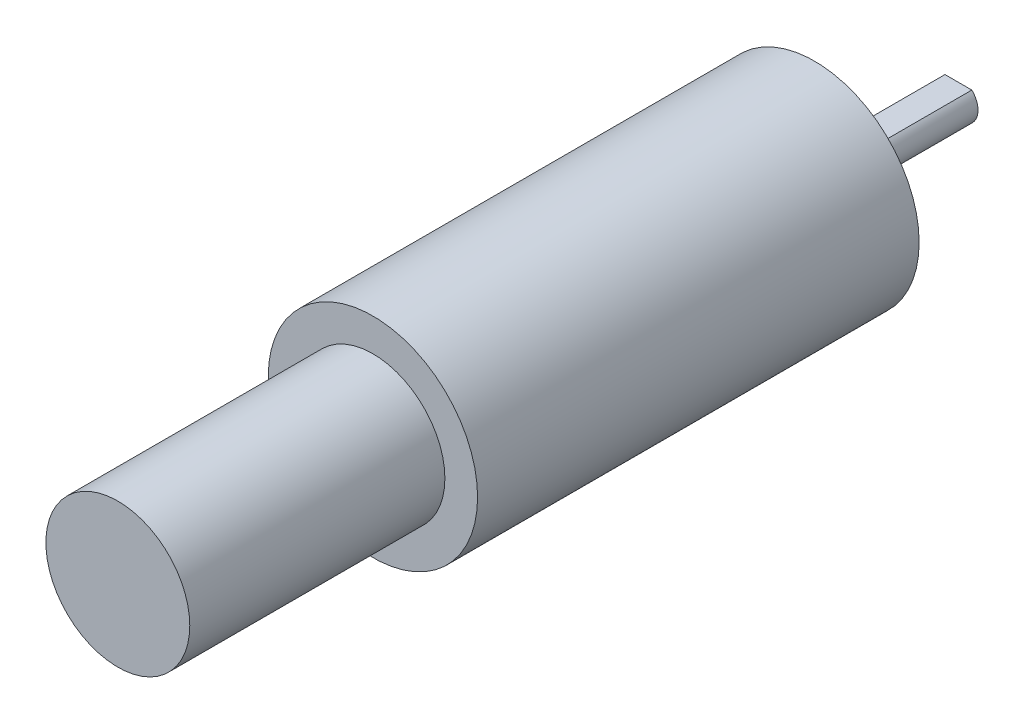
SolidWorks part; units mm, degrees
ref_plane "Front Plane" through (0, 0, 0) normal (0, 0, 1) x (1, 0, 0)
ref_plane "Top Plane" through (0, 0, 0) normal (0, 1, 0) x (1, 0, 0)
ref_plane "Right Plane" through (0, 0, 0) normal (1, 0, 0) x (0, 0, -1)
sketch "Sketch1" plane through (0, 0, 0) normal (0, 0, 1) x (1, 0, 0)
  circle A0 centre (0, 0) radius 16
  dimension "D1" = 32
extrude "Boss-Extrude1" add sketch "Sketch1" along normal blind 67.5
sketch "Sketch2" plane through (0, 0, 0) normal (0, 0, -1) x (-1, 0, 0)
  circle A0 centre (0, 0) radius 9
  dimension "D1" = 18
extrude "Boss-Extrude2" add sketch "Sketch2" along normal blind 1
sketch "Sketch3" plane through (0, 0, -1) normal (0, 0, -1) x (-1, 0, 0)
  circle A0 centre (0, 0) radius 3
  dimension "D1" = 6
extrude "Boss-Extrude3" add sketch "Sketch3" along normal blind 21
sketch "Sketch4" plane through (0, 0, -22) normal (0, 0, -1) x (-1, 0, 0)
  line L0 (-3.1619, 2.1873) -> (3.4651, 2.1873)
  line L1 (3.4651, 2.1873) -> (3.4651, 5.6091)
  line L2 (3.4651, 5.6091) -> (-3.1619, 2.1873)
extrude "Cut-Extrude1" cut sketch "Sketch4" against normal blind 17.698
sketch "Sketch5" plane through (0, 0, 67.5) normal (0, 0, 1) x (1, 0, 0)
  circle A0 centre (0, 0) radius 11
  dimension "D1" = 22
extrude "Boss-Extrude4" add sketch "Sketch5" along normal blind 39
hole_wizard "M3x0.5 Tapped Hole1" positions "Sketch7" profile "Sketch8" tap size "M3x0.5" standard "Ansi Metric"
sketch "Sketch7" plane through (0, 0, 0) normal (0, 0, -1) x (-1, 0, 0)
  point P0 (0, 13)
  dimension "D1" = 13
sketch "Sketch8" plane through (0, 13, 0) normal (1, 0, 0) x (0, 1, 0)
  line L0 (0, 0) -> (0, 8.3711)
  line L1 (0, 8.3711) -> (1.25, 7.62)
  line L2 (1.25, 7.62) -> (1.25, 0)
  line L5 (1.25, 0) -> (0, 0)
  line L10 (0, 8.3711) -> (-1.25, 7.62) construction
  line L11 (0, -6.35) -> (0, 107.95) construction
  dimension "Tap Drill Dia." = 2.5
  dimension "Tap Drill Depth" = 7.62
  dimension "Drill Angle" = 118
pattern_circular "CirPattern1" count 4 over 360 about axis through (0, 0, 0) along (0, 0, 1) of "M3x0.5 Tapped Hole1"
